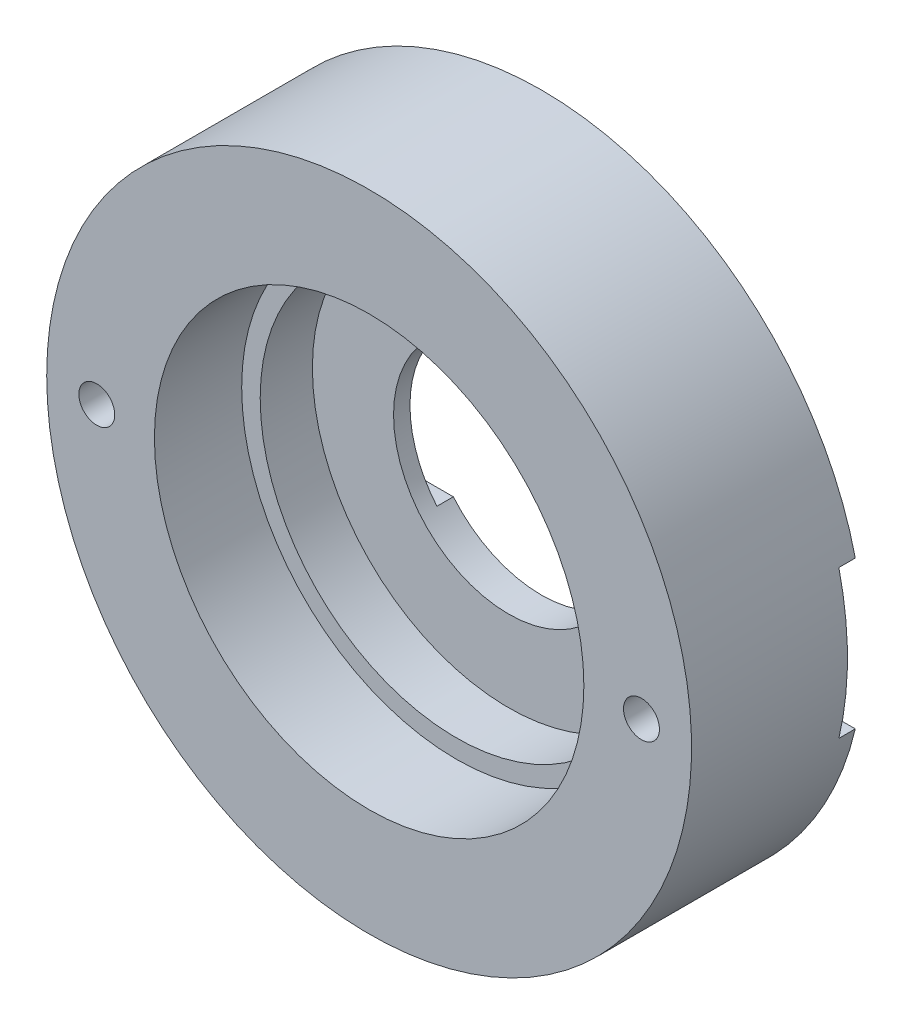
SolidWorks part; units mm, degrees
ref_plane "Front Plane" through (0, 0, 0) normal (0, 0, 1) x (1, 0, 0)
ref_plane "Top Plane" through (0, 0, 0) normal (0, 1, 0) x (1, 0, 0)
ref_plane "Right Plane" through (0, 0, 0) normal (1, 0, 0) x (0, 0, -1)
sketch "Sketch1" plane through (0, 0, 0) normal (0, 1, 0) x (1, 0, 0)
  line L0 (0, 25.4113) -> (0, -24.5124) construction
  line L2 (-7, 4.7005) -> (-19.6178, 4.7005)
  line L3 (-7, 4.7005) -> (-7, 2.7005)
  line L4 (-7, 2.7005) -> (-19.6178, 2.7005)
  line L5 (-19.6178, 4.7005) -> (-19.6178, 2.7005)
  line L6 (-11.938, 2.7005) -> (-19.6178, 2.7005)
  line L7 (-11.938, 2.7005) -> (-11.938, -0.4745)
  line L8 (-11.938, -0.4745) -> (-19.6178, -0.4745)
  line L9 (-19.6178, 2.7005) -> (-19.6178, -0.4745)
  line L10 (-13.0646, -0.4745) -> (-19.6178, -0.4745)
  line L11 (-13.0646, -0.4745) -> (-13.0646, -5.7845)
  line L12 (-13.0646, -5.7845) -> (-19.6178, -5.7845)
  line L13 (-19.6178, -0.4745) -> (-19.6178, -5.7845)
  dimension "D1" = 7
  dimension "D2" = 3.175
  dimension "D3" = 2
  dimension "D4" = 5.31
  dimension "D5" = 11.938
  dimension "D6" = 6.5532
revolve "Revolve1" add sketch "Sketch1" angle 360 about L0
sketch "Sketch2" plane through (0, 0, -4.7005) normal (0, 0, -1) x (-1, 0, 0)
  line L0 (-19.6178, 0) -> (19.6178, 0) construction
  line L1 (0, -19.6178) -> (0, 19.6178) construction
  circle A0 centre (0, 0) radius 19.6178 construction
  circle A1 centre (16.57, 0) radius 1.0922
  circle A2 centre (-16.57, 0) radius 1.0922
  point P11 (0, 0)
  dimension "D1" = 2.1844
  dimension "D3" = 16.57
extrude "Cut-Extrude1" cut sketch "Sketch2" against normal through all
sketch "Sketch3" plane through (0, 0, -4.7005) normal (0, 0, -1) x (-1, 0, 0)
  line L0 (19.6178, 0) -> (-19.6178, 0) construction
  line L1 (0, 19.6178) -> (0, -19.6178) construction
  line L3 (-22.5619, 4.5) -> (22.5619, 4.5)
  line L4 (-22.5619, 4.5) -> (-22.5619, -4.5)
  line L5 (-22.5619, -4.5) -> (22.5619, -4.5)
  line L6 (22.5619, 4.5) -> (22.5619, -4.5)
  line L7 (-22.5619, 4.5) -> (22.5619, -4.5) construction
  line L8 (-22.5619, -4.5) -> (22.5619, 4.5) construction
  circle A0 centre (0, 0) radius 19.6178 construction
  point P7 (0, 0)
  dimension "D1" = 9
extrude "Cut-Extrude2" cut sketch "Sketch3" against normal blind 1
